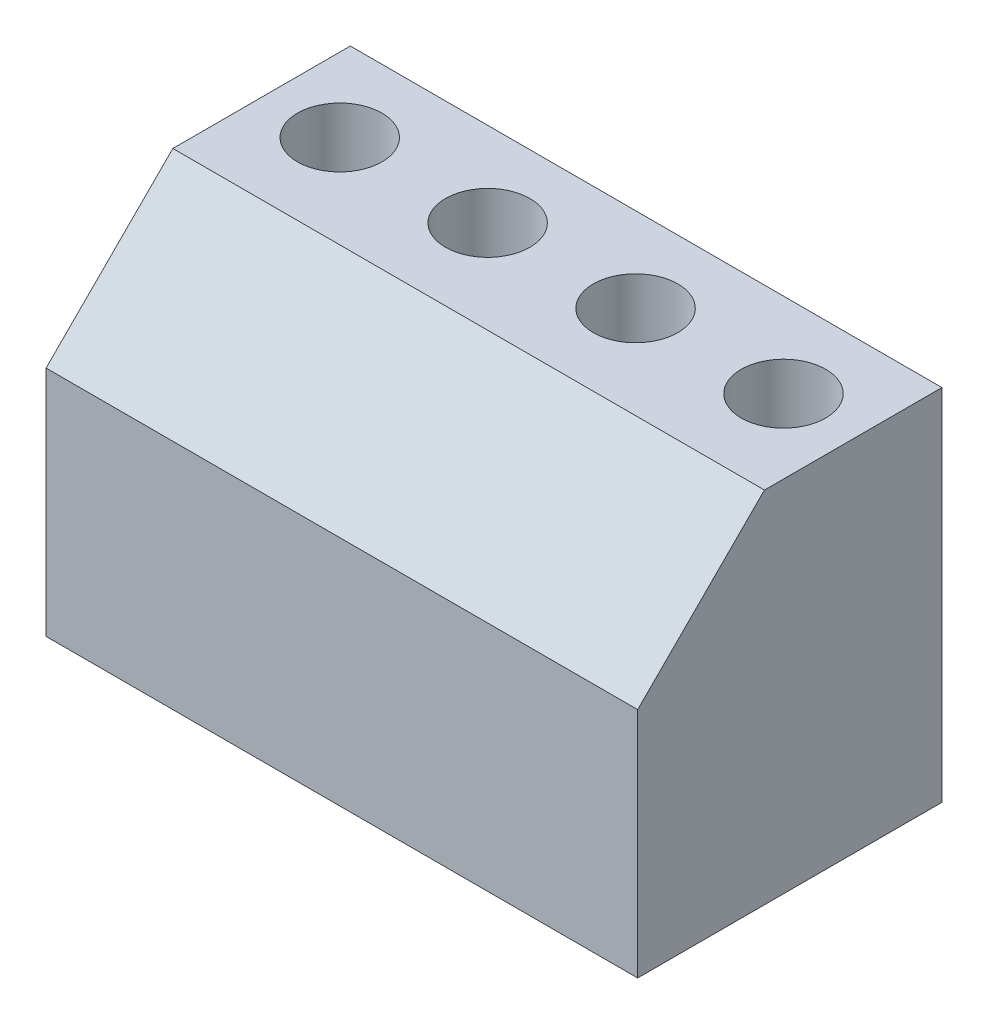
SolidWorks part; units mm, degrees
ref_plane "Front" through (0, 0, 0) normal (0, 0, 1) x (1, 0, 0)
ref_plane "Top" through (0, 0, 0) normal (0, 1, 0) x (1, 0, 0)
ref_plane "Right" through (0, 0, 0) normal (1, 0, 0) x (0, 0, -1)
sketch "Эскиз1" plane through (0, 0, 0) normal (0, 1, 0) x (1, 0, 0)
  line L1 (0, 0) -> (14, 0)
  line L2 (0, 0) -> (0, 7.2)
  line L3 (0, 7.2) -> (14, 7.2)
  line L4 (14, 0) -> (14, 7.2)
  dimension "D1" = 14
  dimension "D2" = 7.2
extrude "Бобышка-Вытянуть1" add sketch "Эскиз1" along normal blind 8.5
chamfer "Фаска1" distance 3 angle 45 1 edges at (7, 8.5, 0)
sketch "Эскиз2" plane through (0, 8.5, 0) normal (0, 1, 0) x (1, 0, 0)
  line L0 (14, 7.2) -> (0, 7.2) construction
  line L1 (0, 7.2) -> (0, 3) construction
  circle A0 centre (1.75, 5.2) radius 1
  circle A1 centre (5.25, 5.2) radius 1
  circle A2 centre (8.75, 5.2) radius 1
  circle A3 centre (12.25, 5.2) radius 1
  dimension "D1" = 2
  dimension "D2" = 2
  dimension "D3" = 2
  dimension "D4" = 2
  dimension "D5" = 3.5
  dimension "D6" = 3.5
  dimension "D7" = 3.5
  dimension "D8" = 2
  dimension "D9" = 1.75
extrude "Вырез-Вытянуть1" cut sketch "Эскиз2" against normal blind 4
